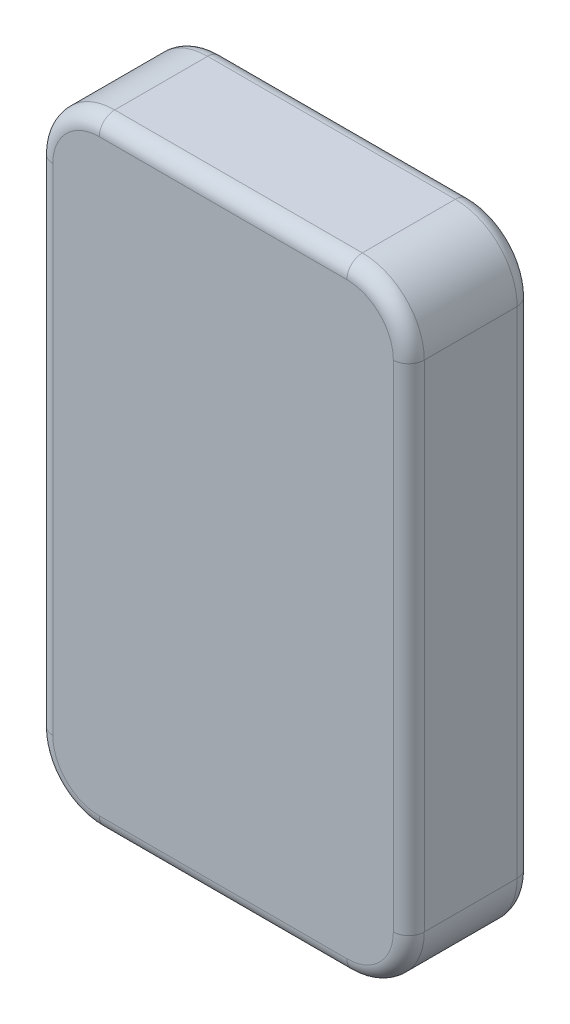
SolidWorks part; units mm, degrees
ref_plane "Front Plane" through (0, 0, 0) normal (0, 0, 1) x (1, 0, 0)
ref_plane "Top Plane" through (0, 0, 0) normal (0, 1, 0) x (1, 0, 0)
ref_plane "Right Plane" through (0, 0, 0) normal (1, 0, 0) x (0, 0, -1)
sketch "Sketch1" plane through (0, 0, 0) normal (0, 0, 1) x (1, 0, 0)
  line L1 (-47.4486, 362.2479) -> (-23.4486, 362.2479)
  line L2 (-47.4486, 362.2479) -> (-47.4486, 322.2479)
  line L3 (-47.4486, 322.2479) -> (-23.4486, 322.2479)
  line L4 (-23.4486, 362.2479) -> (-23.4486, 322.2479)
  dimension "D1" = 24
  dimension "D2" = 40
extrude "Boss-Extrude1" add sketch "Sketch1" against normal blind 8
fillet "Fillet1" radius 4 4 edges at (-23.4486, 362.2479, -4) (-23.4486, 322.2479, -4) (-47.4486, 322.2479, -4) (-47.4486, 362.2479, -4)
fillet "Fillet2" radius 1 16 edges at (-24.6201, 361.0763, -8) (-23.4486, 342.2479, -8) (-24.6201, 323.4195, -8) (-35.4486, 322.2479, -8) (-46.277, 323.4195, -8) (-47.4486, 342.2479, -8) (-46.277, 361.0763, -8) (-24.6201, 323.4195, 0) (-35.4486, 322.2479, 0) (-46.277, 323.4195, 0) (-47.4486, 342.2479, 0) (-46.277, 361.0763, 0) (-35.4486, 362.2479, 0) (-24.6201, 361.0763, 0) (-35.4486, 362.2479, -8) (-23.4486, 342.2479, 0)
